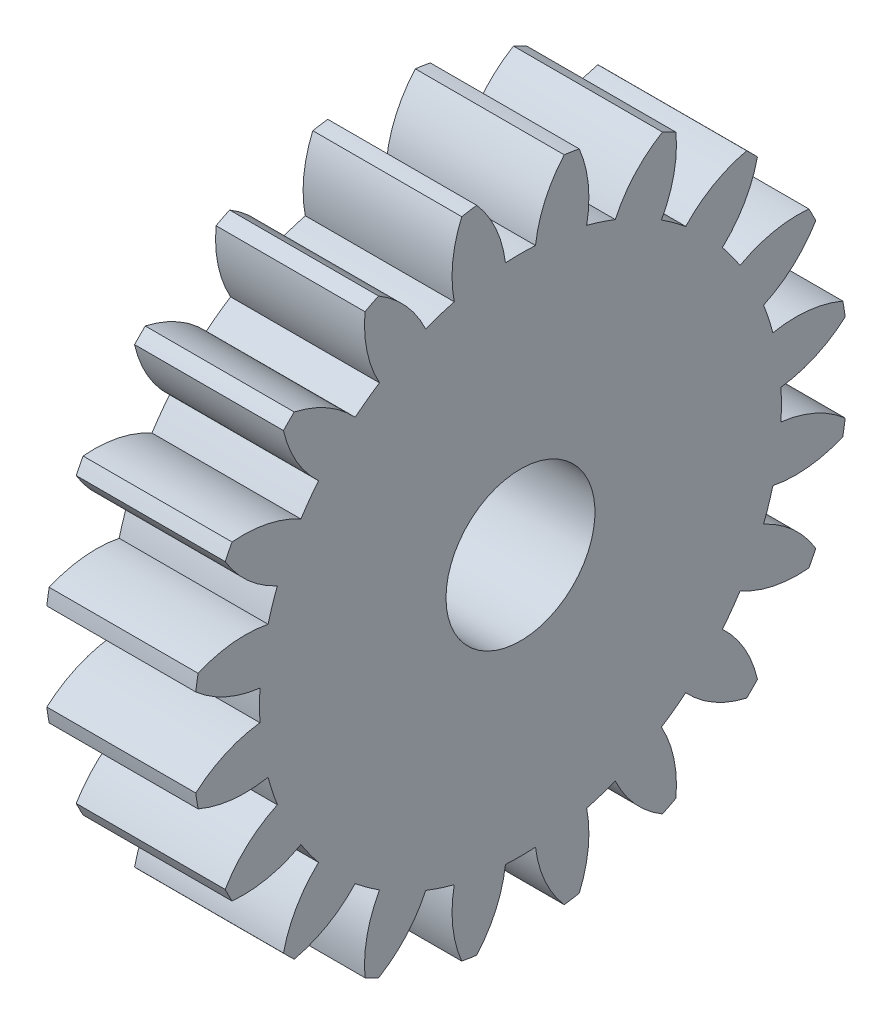
SolidWorks part; units mm, degrees
ref_plane "Plane1" through (0, 0, 0) normal (0, 0, 1) x (1, 0, 0)
ref_plane "Plane2" through (0, 0, 0) normal (0, 1, 0) x (1, 0, 0)
ref_plane "Plane3" through (0, 0, 0) normal (1, 0, 0) x (0, 0, -1)
sketch "HoldingSke" plane through (0, 0, 0) normal (0, 1, 0) x (1, 0, 0)
  line L0 (0, 0) -> (477.3639, -173.7462)
  line L1 (-15, 0) -> (100, 0) construction
  line L2 (0, 0) -> (-2.1039, 2.3779)
  line L3 (0, 0) -> (-11.863, 4.5341)
  line L4 (0, 0) -> (8.1152, 2.9537)
  line L5 (0, 0) -> (-47.5972, -17.7524)
  line L6 (0, 0) -> (-5.2639, -3.5516)
  line L7 (-2.1039, 2.3779) -> (8.8308, 51.9871)
  line L8 (-76.2, 54.61) -> (-69.596, 54.61)
  line L9 (-71.009, 38.7566) -> (-53.1078, 45.2721)
  line L10 (-76.2, 71.12) -> (104.1128, 71.12)
  line L11 (0, 0) -> (-6.35, 0)
  line L12 (-76.2, 101.6) -> (-76.1492, 101.6)
  line L13 (24.9733, 27.94) -> (52.9518, 28.4284)
  line L14 (24.9733, 27.94) -> (25.0241, 27.9398)
  line L15 (24.9733, 27.94) -> (100.4021, 29.52)
  circle A0 centre (0, 0) radius 3.175
  circle A1 centre (0, 0) radius 11.1252
  circle A2 centre (0, 0) radius 38.1
  circle A3 centre (0, 0) radius 3.175
  dimension "MHD" = 22.2504
  dimension "Hub_dia" = 76.2
  dimension "Bore" = 6.35
  dimension "MBD" = 6.35
  dimension "Num_teeth" = 20
  dimension "Pitch" = 508
  dimension "Overall_len" = 50.8
  dimension "Show_teeth" = 20
  dimension "Thickness" = 6.35
  dimension "OAL" = 50.8001
  dimension "T_dim" = 6.604
  dimension "Ap" = 20
  dimension "H" = 19.05
  dimension "Pitch_radius" = 180.3128
  dimension "Width" = 6.35
  dimension "Backlash" = 0.0508
  dimension "Addendum_fac" = 1
  dimension "Dedendum_fac" = 1.2
  dimension "Clearance_fac" = 0.2
  dimension "Dedendum_add" = 0.0508
sketch "BasProSke" plane through (0, 0, 0) normal (0, 1, 0) x (1, 0, 0)
  line L0 (-10, 0) -> (60, 0) construction
  line L1 (0, 0) -> (0, 13.97)
  line L2 (0, 0) -> (6.35, 0)
  line L3 (6.35, 0) -> (6.35, 13.97)
  line L4 (6.35, 13.97) -> (0, 13.97)
  dimension "Thickness" = 6.35
  dimension "Diameter" = 27.94
revolve "Base-Revolve" add sketch "BasProSke" angle 360 about L0
sketch "TooCutSke" plane through (0, 0, 0) normal (1, 0, 0) x (0, 0, -1)
  line L1 (0, 0) -> (0, 107) construction
  line L2 (0, 0) -> (-1.0853, 12.6535) construction
  line L3 (0, 0) -> (-3.9633, 25.0231) construction
  line L4 (-1.0853, 12.6535) -> (-1.9816, 12.5116) construction
  arc A0 (0.6405, 11.1067) -> (-0.6405, 11.1067) centre (0, 0) ccw
  arc A1 (1.8856, 13.8678) -> (-1.8856, 13.8678) centre (0, 0) ccw
  circle A2 centre (0, 0) radius 12.7 construction
  circle A3 centre (0, 0) radius 11.9341 construction
  arc A4 (-0.6405, 11.1067) -> (-1.8856, 13.8678) centre (-5.6834, 10.4939) ccw
  arc A5 (1.8856, 13.8678) -> (0.6405, 11.1067) centre (5.6834, 10.4939) ccw
  dimension "Root_dia" = 22.2504
  dimension "Overcut_dia" = 27.9908
  dimension "Pitch_dia" = 25.4
  dimension "Base_dia" = 23.8682
  dimension "Flank_rad" = 5.08
  dimension "Half_ang" = 9
  dimension "Half_CT" = 0.9075
extrude "ToothCut" cut sketch "TooCutSke" along normal through all
fillet "Breaks" [suppressed] radius 0.0254
fillet "RootFillets" [suppressed] radius 0.3048
pattern_circular "TeethCuts" count 20 every 18 about axis through (-10, 0, 0) along (1, 0, 0) of "ToothCut", "RootFillets", "Breaks"
sketch "HubNeaOneSke" plane through (0, 0, 0) normal (-1, 0, 0) x (0, 0, 1)
  circle A0 centre (0, 0) radius 11.1252
  dimension "Diameter" = 22.2504
extrude "HubNearOne" [suppressed] add sketch "HubNeaOneSke" along normal blind 44.4501
sketch "HubNeaBotSke" plane through (0, 0, 0) normal (-1, 0, 0) x (0, 0, 1)
  circle A0 centre (0, 0) radius 11.1252
  dimension "Diameter" = 22.2504
extrude "HubNearBoth" [suppressed] add sketch "HubNeaBotSke" along normal blind 22.225
ref_plane "FarPln" through (6.35, 0, 0) normal (1, 0, 0) x (0, 0, -1)
sketch "HubFarSke" plane through (6.35, 0, 0) normal (1, 0, 0) x (0, 0, -1)
  circle A0 centre (0, 0) radius 11.1252
  dimension "Diameter" = 22.2504
extrude "HubFar" [suppressed] add sketch "HubFarSke" along normal blind 22.225
sketch "BorSke" plane through (0, 0, 0) normal (1, 0, 0) x (0, 0, -1)
  circle A0 centre (0, 0) radius 3.175
  dimension "Diameter" = 6.35
extrude "Bore" cut sketch "BorSke" along normal mid plane 101.6001
sketch "KeySke" plane through (0, 0, 0) normal (1, 0, 0) x (0, 0, -1)
  line L0 (-0.127, 0) -> (-0.127, 3.429)
  line L1 (-0.127, 3.429) -> (0.127, 3.429)
  line L2 (0.127, 3.429) -> (0.127, 0)
  line L3 (0, 0) -> (0, 34) construction
  line L4 (-0.127, 0) -> (0.127, 0)
  dimension "Offset" = 3.429
  dimension "Width" = 0.254
extrude "Keyway" [suppressed] cut sketch "KeySke" along normal mid plane 101.6001
pattern_circular "Keyway2" [suppressed] count 2 every 90 about axis through (-10, 0, 0) along (1, 0, 0)
equation "' \"Pitch@HoldingSke\" = 4"
equation "' \"Num_teeth@HoldingSke\" = 12"
equation "' \"Ap@HoldingSke\" =  20"
equation "' \"Ap@HoldingSke\" = 20"
equation "' \"Width@HoldingSke\" = 0.5"
equation "' \"Hub_dia@HoldingSke\"= 1"
equation "' \"Hub_dia@HoldingSke\" = 1"
equation "' \"Overall_len@HoldingSke\" = 1.0"
equation "' \"Bore@HoldingSke\" = 0.75"
equation "' \"T_dim@HoldingSke\" = 0.85"
equation "' \"Width@KeySke\" = 0.25"
equation "' \"Show_teeth@HoldingSke\" = 13"
equation "' \"Backlash@HoldingSke\" = 0.009"
equation "' \"Addendum_fac@HoldingSke\" = 1.0"
equation "' \"Dedendum_fac@HoldingSke\" = 1.25"
equation "' \"Dedendum_add@HoldingSke\" = 0.00005"
equation "' \"Clearance_fac@HoldingSke\" = 0.25"
equation "' \"Pitch@HoldingSke\" = 0.5"
equation "' \"Num_teeth@HoldingSke\" = 23"
equation "' \"Show_teeth@HoldingSke\" = 23"
equation "' \"Backlash@HoldingSke\" = 0.0375"
equation "\"Overcut_dia@TooCutSke\" = (\"Num_teeth@HoldingSke\" + 2 * \"Addendum_fac@HoldingSke\") / \"Pitch@HoldingSke\" + 0.002"
equation "\"Pitch_dia@TooCutSke\" = \"Num_teeth@HoldingSke\" / \"Pitch@HoldingSke\""
equation "\"Base_dia@TooCutSke\" = \"Num_teeth@HoldingSke\" / \"Pitch@HoldingSke\" * cos((\"Ap@HoldingSke\"  * 3.14159265 / 180))"
equation "\"Root_dia@TooCutSke\" = (\"Num_teeth@HoldingSke\" + 2) / \"Pitch@HoldingSke\" - 2 * (\"Addendum_fac@HoldingSke\" + \"Dedendum_fac@HoldingSke\") / \"Pitch@HoldingSke\" - \"Dedendum_add@HoldingSke\" * 2"
equation "\"Half_ang@TooCutSke\" = 180 / \"Num_teeth@HoldingSke\""
equation "\"Half_CT@TooCutSke\" = \"Num_teeth@HoldingSke\" / \"Pitch@HoldingSke\" * sin((3.14159265 / 2 / \"Num_teeth@HoldingSke\")) / 2 - 7 * \"Backlash@HoldingSke\" / 4"
equation "\"Flank_rad@TooCutSke\" = \"Num_teeth@HoldingSke\" / \"Pitch@HoldingSke\" / 5"
equation "\"Radius@RootFillets\" = \"Clearance_fac@HoldingSke\" / \"Pitch@HoldingSke\" + \"Dedendum_add@HoldingSke\""
equation "\"Break_rad@Breaks\" = 0.02 / \"Pitch@HoldingSke\""
equation "\"Thickness@HoldingSke\" = \"Width@HoldingSke\""
equation "\"OAL@HoldingSke\" = \"Thickness@HoldingSke\""
equation "\"MHD@HoldingSke\" = (\"Num_teeth@HoldingSke\" + 2) / \"Pitch@HoldingSke\" - 2 * (\"Addendum_fac@HoldingSke\" + \"Dedendum_fac@HoldingSke\")  / \"Pitch@HoldingSke\" - \"Dedendum_add@HoldingSke\" * 2"
equation "\"MBD@HoldingSke\" = (\"Num_teeth@HoldingSke\" + 2) / \"Pitch@HoldingSke\" - 2 * (\"Addendum_fac@HoldingSke\" + \"Dedendum_fac@HoldingSke\")  / \"Pitch@HoldingSke\" - \"Dedendum_add@HoldingSke\" * 2 - 0.002"
equation "\"MHD@HoldingSke\" = ((sgn( \"MHD@HoldingSke\" - \"Hub_dia@HoldingSke\" )-1)*( \"MHD@HoldingSke\" - \"Hub_dia@HoldingSke\" ))/-2+ \"Hub_dia@HoldingSke\""
equation "\"MBD@HoldingSke\" = ((sgn( \"MBD@HoldingSke\" - \"Bore@HoldingSke\" )-1)*( \"MBD@HoldingSke\" - \"Bore@HoldingSke\" ))/-2+ \"Bore@HoldingSke\""
equation "\"OAL@HoldingSke\" = ((sgn( \"OAL@HoldingSke\" - \"Overall_len@HoldingSke\" )+1)*( \"OAL@HoldingSke\" - \"Overall_len@HoldingSke\" ))/2 + \"Overall_len@HoldingSke\" + 0.000002"
equation "\"Num_teeth@TeethCuts\" = int( \"Show_teeth@HoldingSke\" ) + 1"
equation "\"Num_teeth@TeethCuts\" = ((sgn( \"Num_teeth@TeethCuts\" - \"Num_teeth@HoldingSke\" )-1)*( \"Num_teeth@TeethCuts\" - \"Num_teeth@HoldingSke\" ))/-2+ \"Num_teeth@HoldingSke\""
equation "\"Num_teeth@TeethCuts\" = ((sgn( \"Num_teeth@TeethCuts\" - 2.0)+1)*( \"Num_teeth@TeethCuts\" - 2.0))/2 +2.0"
equation "\"Angle@TeethCuts\" = 360.0 / \"Num_teeth@HoldingSke\""
equation "\"Diameter@BasProSke\" = (\"Num_teeth@HoldingSke\" + 2 * \"Addendum_fac@HoldingSke\") / \"Pitch@HoldingSke\""
equation "\"Thickness@BasProSke\"  = \"Thickness@HoldingSke\""
equation "' \"Fillet_rad@BasProSke\" =  \"Thickness@HoldingSke\" * 0.05"
equation "' \"Fillet_rad@BasProSke\" = \"Thickness@HoldingSke\" * 0.05"
equation "\"MHD@HoldingSke\" = ((sgn( \"MHD@HoldingSke\" - \"Root_dia@TooCutSke\" )-1)*( \"MHD@HoldingSke\" - \"Root_dia@TooCutSke\" ))/-2+ \"Root_dia@TooCutSke\""
equation "\"Diameter@HubNeaOneSke\" = \"MHD@HoldingSke\""
equation "\"Length@HubNearOne\" = \"OAL@HoldingSke\" - \"Thickness@BasProSke\""
equation "\"Diameter@HubNeaBotSke\" = \"MHD@HoldingSke\""
equation "\"Length@HubNearBoth\" = ( \"OAL@HoldingSke\" - \"Thickness@BasProSke\" ) / 2.0"
equation "\"Thickness@FarPln\" = \"Thickness@BasProSke\""
equation "\"Diameter@HubFarSke\" = \"MHD@HoldingSke\""
equation "\"Length@HubFar\" = ( \"OAL@HoldingSke\" - \"Thickness@BasProSke\" ) / 2.0"
equation "\"Diameter@BorSke\" = \"MBD@HoldingSke\""
equation "\"D1@Bore\" = \"OAL@HoldingSke\" * 2.0"
equation "\"D1@Keyway\" = \"OAL@HoldingSke\" * 2.0"
equation "\"Offset@KeySke\" = \"T_dim@HoldingSke\" - \"MBD@HoldingSke\" / 2.0"
